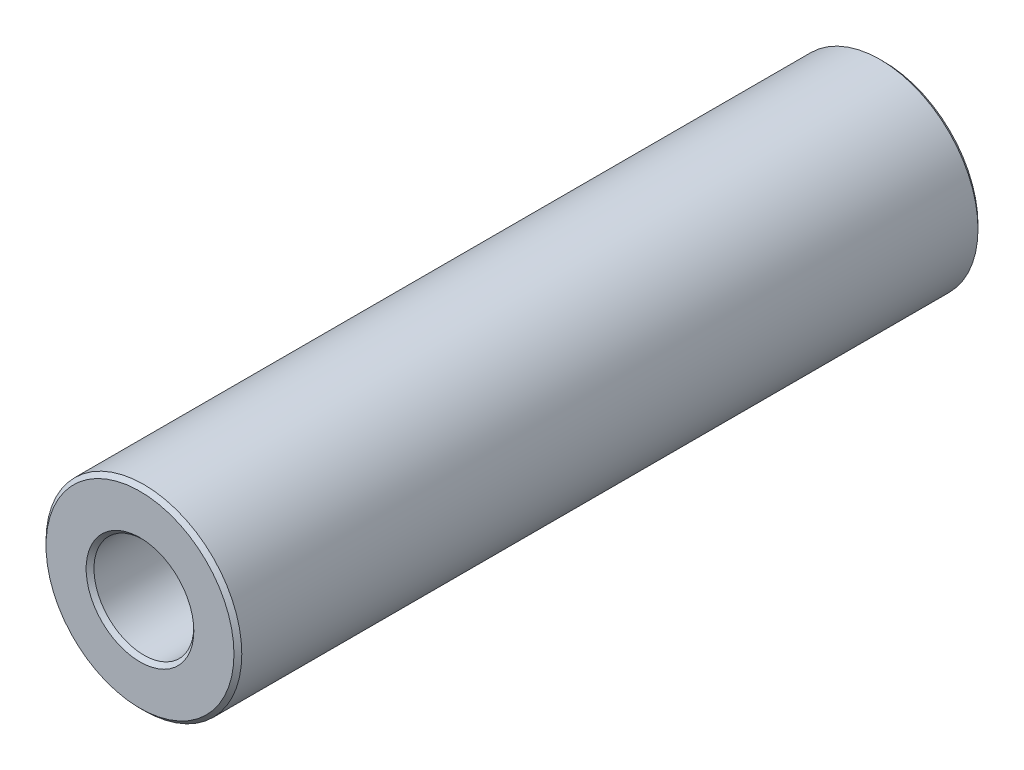
SolidWorks part; units mm, degrees
material "6061-T6 (SS)"
ref_plane "Front Plane" through (0, 0, 0) normal (0, 0, 1) x (1, 0, 0)
ref_plane "Top Plane" through (0, 0, 0) normal (0, 1, 0) x (1, 0, 0)
ref_plane "Right Plane" through (0, 0, 0) normal (1, 0, 0) x (0, 0, -1)
sketch "Sketch1" plane through (0, 0, 0) normal (0, 0, 1) x (1, 0, 0)
  circle A0 centre (0, 0) radius 2.55
  circle A1 centre (0, 0) radius 5
  dimension "D1" = 5.1
  dimension "D2" = 10
extrude "Boss-Extrude1" add sketch "Sketch1" along normal blind 38
chamfer "Chamfer1" distance 0.2 angle 45 4 edges at (5, 0, 0) (2.55, 0, 0) (2.55, 0, 38) (5, 0, 38)
